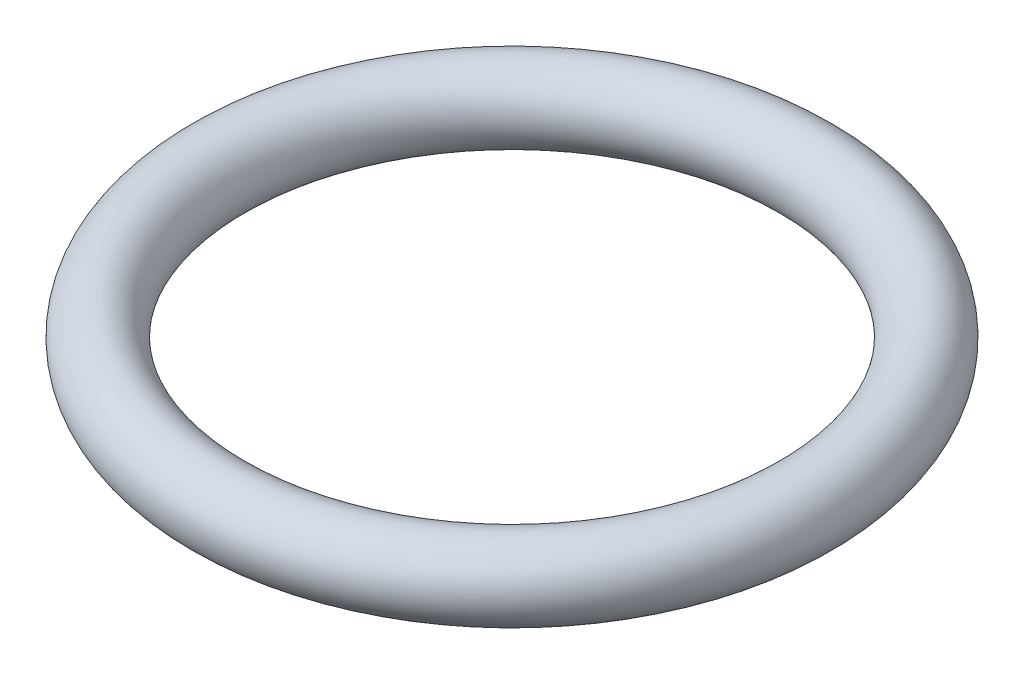
SolidWorks part; units mm, degrees
ref_plane "前视基准面" through (0, 0, 0) normal (0, 0, 1) x (1, 0, 0)
ref_plane "上视基准面" through (0, 0, 0) normal (0, 1, 0) x (1, 0, 0)
ref_plane "右视基准面" through (0, 0, 0) normal (1, 0, 0) x (0, 0, -1)
other "Configuration Table"
sketch "草图1" plane through (0, 0, 0) normal (0, 0, 1) x (1, 0, 0)
  line L0 (0, 16.8791) -> (0, -14.1318) construction
  circle A0 centre (-26, 0) radius 3.25
  point P2 (0, 0)
  dimension "D1" = 6.5
  dimension "D2" = 26
revolve "旋转1" add sketch "草图1" angle 360 about L0
